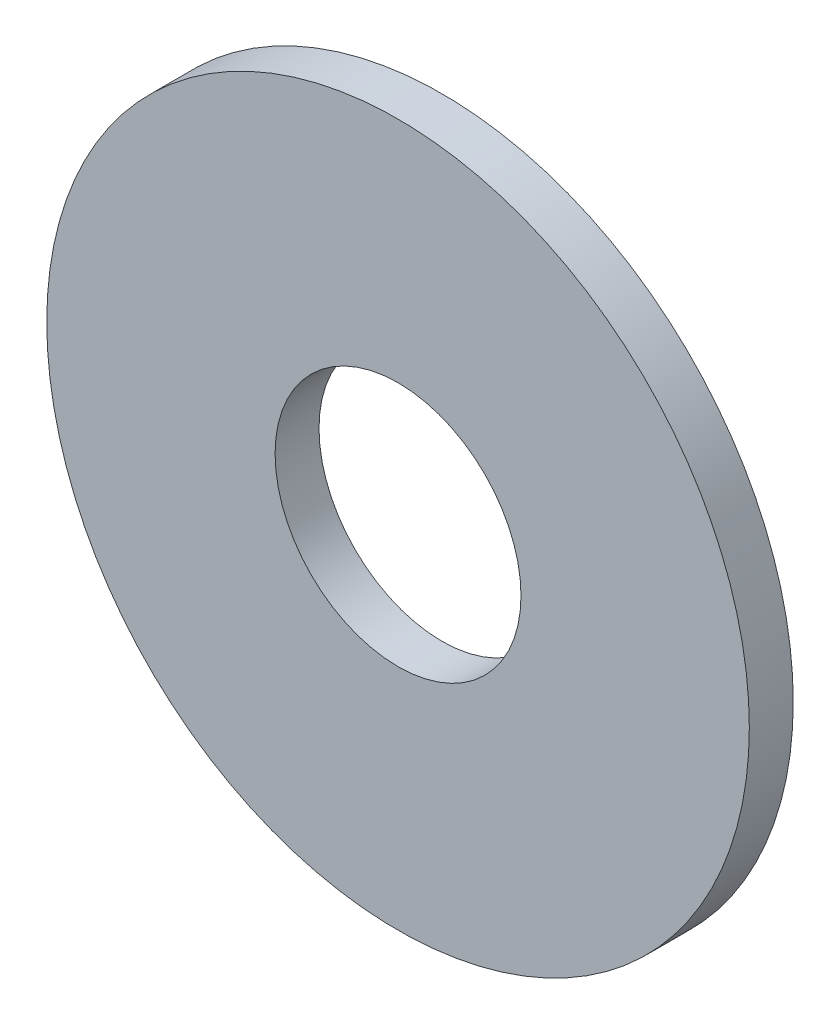
SolidWorks part; units mm, degrees
ref_plane "Plan de face" through (0, 0, 0) normal (0, 0, 1) x (1, 0, 0)
ref_plane "Plan de dessus" through (0, 0, 0) normal (0, 1, 0) x (1, 0, 0)
ref_plane "Plan de droite" through (0, 0, 0) normal (1, 0, 0) x (0, 0, -1)
sketch "Esquisse1" plane through (0, 0, 0) normal (0, 0, 1) x (1, 0, 0)
  circle A0 centre (0, 0) radius 12
  dimension "D1" = 24
extrude "Boss.-Extru.1" add sketch "Esquisse1" along normal blind 1.5
sketch "Esquisse2" plane through (0, 0, 1.5) normal (0, 0, 1) x (1, 0, 0)
  circle A0 centre (0, 0) radius 4.2
  dimension "D1" = 8.4
extrude "Enlèv. mat.-Extru.1" cut sketch "Esquisse2" against normal blind 1.5
